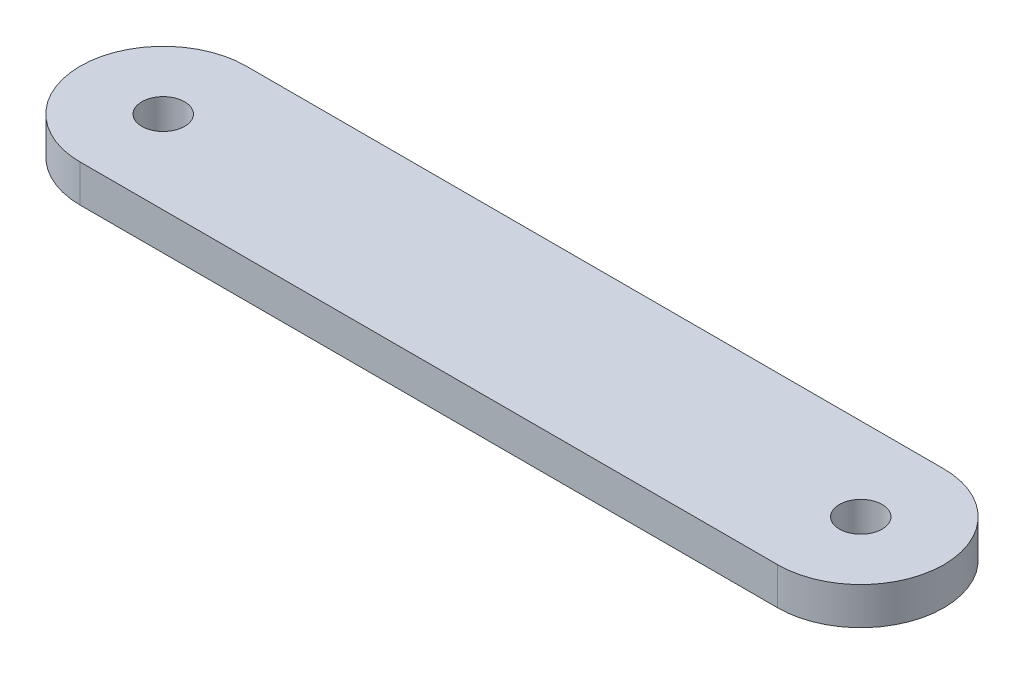
SolidWorks part; units mm, degrees
ref_plane "Front Plane" through (0, 0, 0) normal (0, 0, 1) x (1, 0, 0)
ref_plane "Top Plane" through (0, 0, 0) normal (0, 1, 0) x (1, 0, 0)
ref_plane "Right Plane" through (0, 0, 0) normal (1, 0, 0) x (0, 0, -1)
sketch "Sketch2" plane through (0, 0, 0) normal (0, 1, 0) x (1, 0, 0)
  line L0 (42, 0) -> (-42, 0) construction
  line L1 (42, 10) -> (-42, 10)
  line L2 (42, -10) -> (-42, -10)
  arc A0 (42, 10) -> (42, -10) centre (42, 0) cw
  arc A1 (-42, 10) -> (-42, -10) centre (-42, 0) ccw
  point P4 (0, 0)
  dimension "D1" = 84
  dimension "D2" = 10
  dimension "D3" = 10
extrude "Boss-Extrude1" add sketch "Sketch2" along normal blind 4.5
sketch "Sketch3" plane through (0, 4.5, 0) normal (0, 1, 0) x (1, 0, 0)
  circle A0 centre (42, 0) radius 2.575
  circle A1 centre (-42, 0) radius 2.575
  dimension "D1" = 5.15
extrude "5.15mm holes" cut sketch "Sketch3" against normal through all
